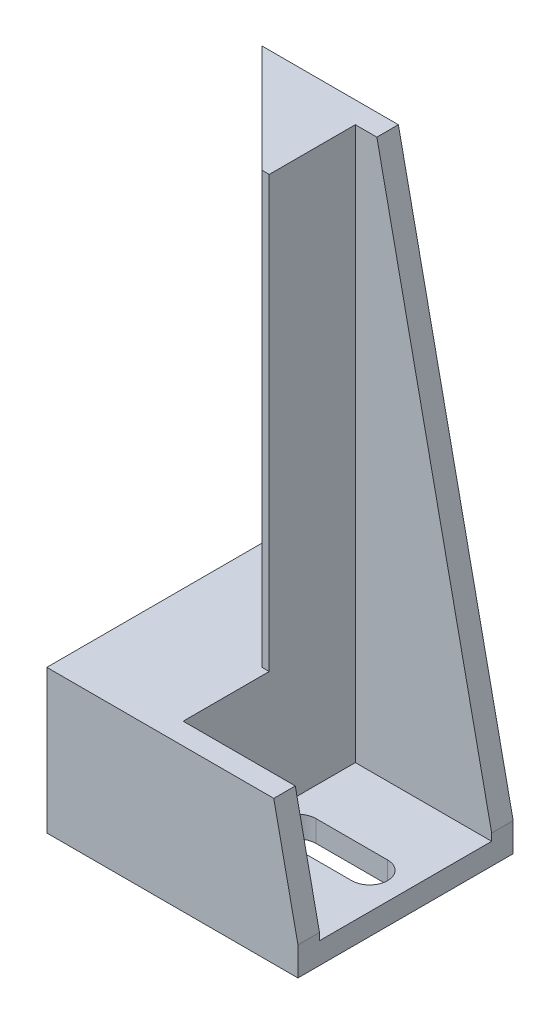
SolidWorks part; units mm, degrees
material "ABS"
ref_plane "Front Plane" through (0, 0, 0) normal (0, 0, 1) x (1, 0, 0)
ref_plane "Top Plane" through (0, 0, 0) normal (0, 1, 0) x (1, 0, 0)
ref_plane "Right Plane" through (0, 0, 0) normal (1, 0, 0) x (0, 0, -1)
sketch "Sketch1" plane through (0, 0, 0) normal (0, 0, 1) x (1, 0, 0)
  line L0 (0, 0) -> (25.4, 0)
  line L1 (25.4, 0) -> (25.4, 5.08)
  line L2 (25.4, 5.08) -> (5.08, 101.6)
  line L3 (5.08, 101.6) -> (0, 101.6)
  line L4 (0, 101.6) -> (0, 0)
  dimension "D1" = 25.4
  dimension "D2" = 5.08
  dimension "D3" = 101.6
extrude "Boss-Extrude1" add sketch "Sketch1" along normal blind 38.1
shell "Shell1" thickness 3.81
sketch "Sketch2" plane through (0, 0, 0) normal (0, -1, 0) x (1, 0, 0)
  line L0 (6.35, 19.05) -> (19.05, 19.05) construction
  line L1 (6.35, 22.225) -> (19.05, 22.225)
  line L2 (6.35, 15.875) -> (19.05, 15.875)
  line L4 (0, 38.1) -> (25.4, 38.1) construction
  line L5 (0, 38.1) -> (0, 0) construction
  arc A0 (6.35, 22.225) -> (6.35, 15.875) centre (6.35, 19.05) ccw
  arc A1 (19.05, 15.875) -> (19.05, 22.225) centre (19.05, 19.05) ccw
  point P2 (12.7, 19.05)
  point P12 (12.7, 38.1)
  point P16 (0, 19.05)
  dimension "D1" = 3.175
  dimension "D2" = 12.7
extrude "Cut-Extrude1" cut sketch "Sketch2" against normal up to surface (3.81 mm away) up to face at (12.7, 3.81, 19.05)
sketch "Sketch3" plane through (0, 101.6, 0) normal (0, 1, 0) x (1, 0, 0)
  line L0 (0, -19.05) -> (-19.05, 0)
  line L1 (0, -38.1) -> (0, 0) construction
  line L2 (-19.05, 0) -> (0, 0)
  line L3 (0, 0) -> (0, -38.1)
  line L4 (0, -38.1) -> (-19.05, -38.1)
  line L5 (-19.05, -38.1) -> (0, -19.05)
  line M5 (0, 0) -> (0, -38.1)
  dimension "D1" = 19.05
extrude "Boss-Extrude2" add sketch "Sketch3" against normal up to surface (101.6 mm away) contours L2 L0 M5 | L5 L4 M5 up to face at (12.7, 0, 19.05)
sketch "Sketch5" plane through (0, 101.6, 0) normal (0, 1, 0) x (1, 0, 0)
  line L0 (1.27, -3.81) -> (1.27, -34.29)
  line L1 (25.4, 0) -> (5.08, 0) construction
  line L3 (25.4, -3.81) -> (25.4, -34.29)
  line L4 (25.4, -38.1) -> (25.4, 0) construction
  line L5 (25.4, -34.29) -> (1.27, -34.29)
  line L6 (3.81, -34.29) -> (21.59, -34.29) construction
  line L7 (25.4, -3.81) -> (1.27, -3.81)
  dimension "D1" = 1.27
  dimension "D2" = 3.81
extrude "Cut-Extrude2" cut sketch "Sketch5" against normal up to surface (97.79 mm away) up to face at (12.7, 3.81, 25.9233)
sketch "Sketch6" plane through (0, 0, 0) normal (0, -1, 0) x (1, 0, 0)
  line L0 (-19.05, 0) -> (0, 19.05)
  line L1 (0, 19.05) -> (-19.05, 38.1)
  line L2 (-19.05, 38.1) -> (-19.05, 0)
extrude "Boss-Extrude3" add sketch "Sketch6" against normal blind 25.4
sketch "Sketch9" plane through (0, 101.6, 0) normal (0, 1, 0) x (1, 0, 0)
  line L1 (-19.05, -38.1) -> (-19.05, 0) construction
  line L2 (-19.05, -19.05) -> (25.4, -19.05)
  line L3 (-19.05, -19.05) -> (-19.05, -38.1)
  line L4 (-19.05, -38.1) -> (25.4, -38.1)
  line L5 (25.4, -19.05) -> (25.4, -38.1)
extrude "Cut-Extrude4" cut sketch "Sketch9" against normal up to surface (76.2 mm away) up to face at (-12.7, 25.4, 19.05)
